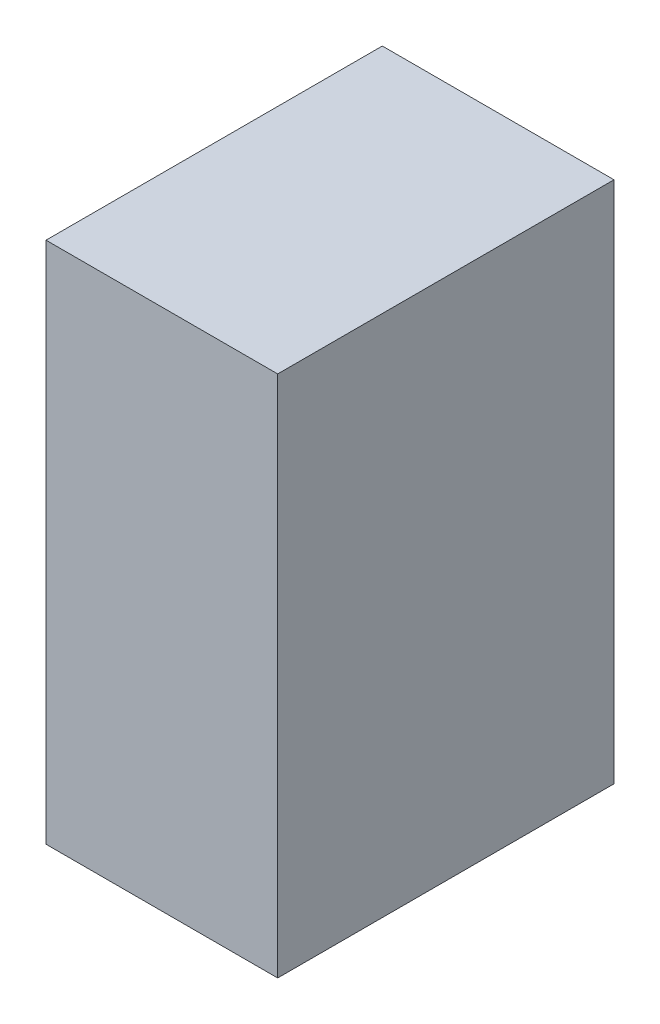
SolidWorks part; units mm, degrees
ref_plane "Front Plane" through (0, 0, 0) normal (0, 0, 1) x (1, 0, 0)
ref_plane "Top Plane" through (0, 0, 0) normal (0, 1, 0) x (1, 0, 0)
ref_plane "Right Plane" through (0, 0, 0) normal (1, 0, 0) x (0, 0, -1)
sketch "Sketch1" plane through (0, 0, 0) normal (0, 1, 0) x (1, 0, 0)
  line L1 (-19.685, -28.575) -> (19.685, -28.575)
  line L2 (-19.685, -28.575) -> (-19.685, 28.575)
  line L3 (-19.685, 28.575) -> (19.685, 28.575)
  line L4 (19.685, -28.575) -> (19.685, 28.575)
  line L5 (-19.685, -28.575) -> (19.685, 28.575) construction
  line L6 (-19.685, 28.575) -> (19.685, -28.575) construction
  point P0 (0, 0)
  dimension "D1" = 57.15
  dimension "D2" = 39.37
extrude "Boss-Extrude1" add sketch "Sketch1" along normal blind 44.45 and the other way blind 44.45
